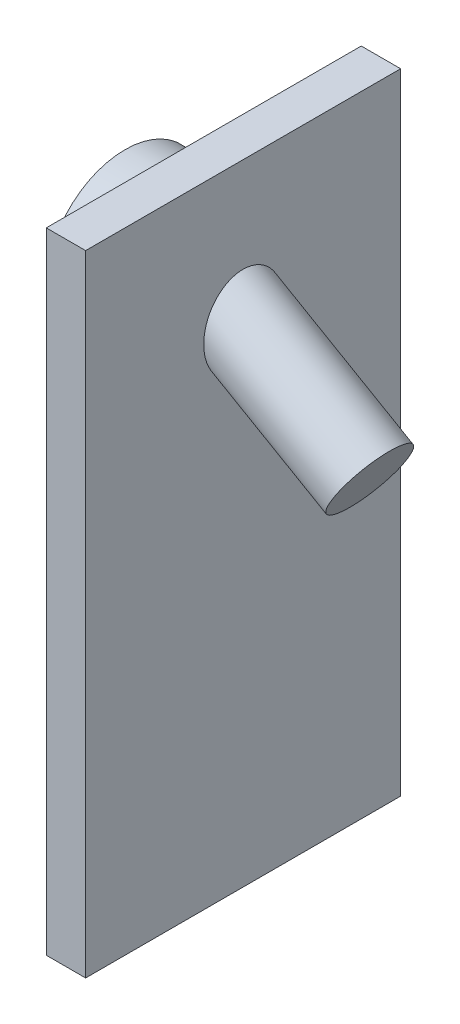
SolidWorks part; units mm, degrees
ref_plane "Front Plane" through (0, 0, 0) normal (0, 0, 1) x (1, 0, 0)
ref_plane "Top Plane" through (0, 0, 0) normal (0, 1, 0) x (1, 0, 0)
ref_plane "Right Plane" through (0, 0, 0) normal (1, 0, 0) x (0, 0, -1)
sketch "Sketch1" plane through (0, 0, 0) normal (0, 0, 1) x (1, 0, 0)
  line L0 (0, 0) -> (0, 50.8)
  line L1 (0, 0) -> (-3.175, 0)
  line L2 (-3.175, 0) -> (-3.175, 50.8)
  line L3 (-3.175, 50.8) -> (0, 50.8)
  dimension "D1" = 50.8
  dimension "D2" = 3.175
extrude "Boss-Extrude1" add sketch "Sketch1" along normal blind 25.4
sketch "Sketch2" plane through (-3.175, 0, 0) normal (-1, 0, 0) x (0, 0, 1)
  circle A0 centre (12.7, 40.3862) radius 6.35
  dimension "D1" = 12.7
extrude "Boss-Extrude2" add sketch "Sketch2" along normal blind 6.35 contours A0
ref_plane "Plane1" through (0, 0, 0) normal (1, 0, 0) x (0, 0, -1)
ref_plane "Plane2" through (0, 0, 12.7) normal (0, 0, 1) x (1, 0, 0)
sketch "Sketch5" plane through (0, 0, 12.7) normal (0, 0, 1) x (1, 0, 0)
  line L0 (0, 43.1462) -> (11.7954, 36.3362)
  line L1 (11.7954, 36.3362) -> (10.2079, 33.5865)
  line L2 (10.2079, 33.5865) -> (0, 39.4801)
  line L3 (0, 39.4801) -> (0, 43.1462)
  line L4 (11.7954, 36.3362) -> (0.6456, 36.3362) construction
  dimension "D1" = 3.175
  dimension "D2" = 30
revolve "Revolve2" add sketch "Sketch5" angle 360 about L2
